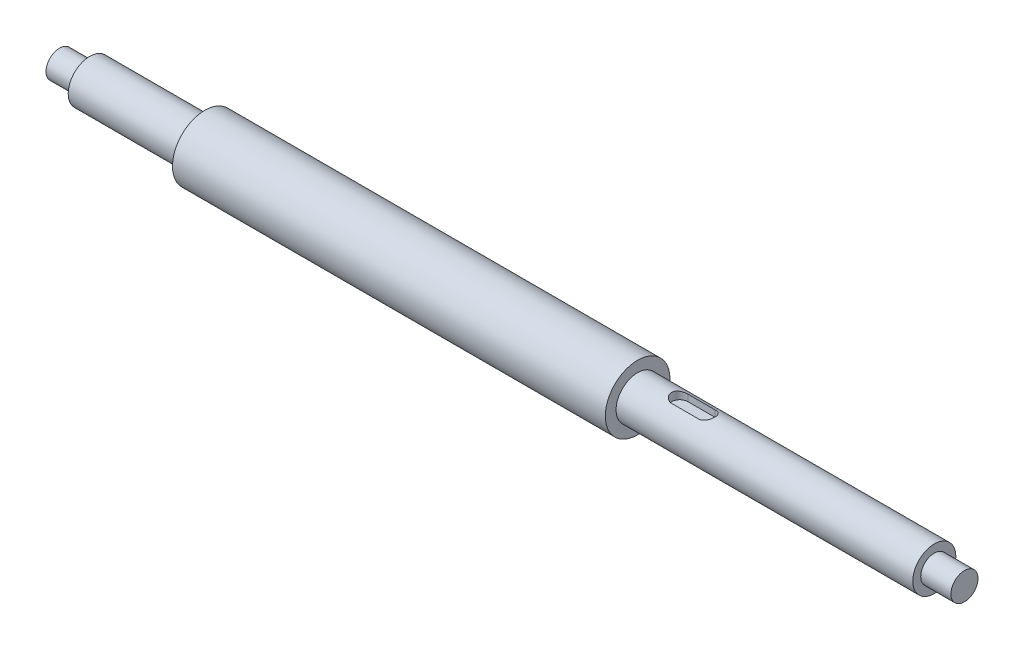
SolidWorks part; units mm, degrees
ref_plane "Front Plane" through (0, 0, 0) normal (0, 0, 1) x (1, 0, 0)
ref_plane "Top Plane" through (0, 0, 0) normal (0, 1, 0) x (1, 0, 0)
ref_plane "Right Plane" through (0, 0, 0) normal (1, 0, 0) x (0, 0, -1)
sketch "Sketch1" plane through (0, 0, 0) normal (1, 0, 0) x (0, 0, -1)
  circle A0 centre (0, 0) radius 9.525
  dimension "D1" = 19.05
extrude "Boss-Extrude1" add sketch "Sketch1" along normal blind 266.7
ref_plane "Plane1" through (133.35, 0, 0) normal (-1, 0, 0) x (0, 0, 1)
sketch "Sketch4" plane through (0, 0, 0) normal (-1, 0, 0) x (0, 0, 1)
  circle A0 centre (0, 0) radius 6.35
  circle A1 centre (0, 0) radius 9.525 construction
  circle A2 centre (0, 0) radius 9.525
  dimension "D1" = 12.7
extrude "Cut-Extrude3" cut sketch "Sketch4" against normal blind 42.799
sketch "Sketch5" plane through (0, 0, 0) normal (-1, 0, 0) x (0, 0, 1)
  circle A0 centre (0, 0) radius 4
  circle A1 centre (0, 0) radius 6.35 construction
  circle A2 centre (0, 0) radius 6.35
  dimension "D1" = 8
extrude "Cut-Extrude4" cut sketch "Sketch5" against normal blind 8.89
sketch "Sketch6" plane through (266.7, 0, 0) normal (1, 0, 0) x (0, 0, -1)
  circle A0 centre (0, 0) radius 6.35
  circle A1 centre (0, 0) radius 9.525 construction
  circle A2 centre (0, 0) radius 9.525
  dimension "D1" = 12.7
extrude "Cut-Extrude5" cut sketch "Sketch6" against normal blind 96.3295
mirror "Mirror1" about plane through (133.35, 0, 0) normal (-1, 0, 0) of "Cut-Extrude4"
ref_plane "Plane2" through (0, 6.35, 0) normal (0, 1, 0) x (1, 0, 0)
sketch "Sketch7" plane through (0, 6.35, 0) normal (0, 1, 0) x (1, 0, 0)
  line L0 (170.3705, -9.525) -> (170.3705, 9.525) construction
  line L1 (257.81, -6.35) -> (257.81, 6.35) construction
  line L2 (170.3705, -9.525) -> (170.3705, 9.525) construction
  line L3 (257.81, -6.35) -> (257.81, 6.35) construction
  line L4 (257.81, 0) -> (170.3705, 0) construction
  line L5 (182.7911, 0) -> (190.7286, 0) construction
  line L6 (182.7911, 2.3812) -> (190.7286, 2.3812)
  line L7 (182.7911, -2.3813) -> (190.7286, -2.3813)
  line L8 (266.7, -4) -> (266.7, 4) construction
  arc A0 (182.7911, 2.3812) -> (182.7911, -2.3813) centre (182.7911, 0) ccw
  arc A1 (190.7286, -2.3813) -> (190.7286, 2.3812) centre (190.7286, 0) ccw
  point P8 (186.7599, 0)
  dimension "D1" = 7.9375
  dimension "D2" = 4.7625
  dimension "D3" = 75.9714
extrude "Cut-Extrude6" cut sketch "Sketch7" against normal blind 2.3876
